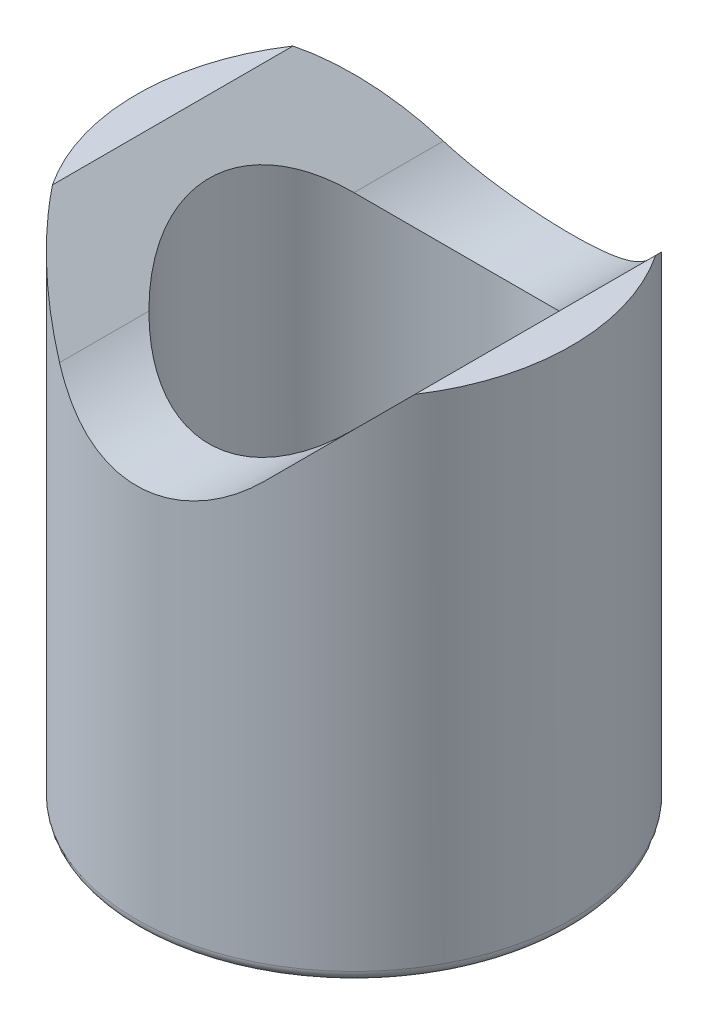
SolidWorks part; units mm, degrees
material "1060 Сплав"
ref_plane "Спереди" through (0, 0, 0) normal (0, 0, 1) x (1, 0, 0)
ref_plane "Сверху" through (0, 0, 0) normal (0, 1, 0) x (1, 0, 0)
ref_plane "Справа" through (0, 0, 0) normal (1, 0, 0) x (0, 0, -1)
sketch "Эскиз1" plane through (0, 0, 0) normal (0, 1, 0) x (1, 0, 0)
  circle A0 centre (0, 0) radius 6
  circle A1 centre (0, 0) radius 4
extrude "Бобышка-Вытянуть1" add sketch "Эскиз1" along normal blind 15
cosmetic thread "Условное изображение резьбы1" parameters "D2"=24
sketch "Эскиз2" plane through (0, 0, 0) normal (0, 0, 1) x (1, 0, 0)
  line L0 (5, 14) -> (2.8284, 11.8284)
  line L1 (-2.8284, 11.8284) -> (-5, 14)
  line L2 (6, 15) -> (-6, 15) construction
  line L3 (-5, 14) -> (-7.9166, 14)
  line L4 (5, 14) -> (8.0781, 14)
  line L5 (-7.9166, 14) -> (-7.9166, 18.7424)
  line L6 (-7.9166, 18.7424) -> (8.0781, 18.7424)
  line L7 (8.0781, 18.7424) -> (8.0781, 14)
  arc A0 (2.8284, 11.8284) -> (-2.8284, 11.8284) centre (0, 14.6569) cw
  point P12 (0, 9)
  dimension "D5" = 4
  dimension "D1" = 90
  dimension "D2" = 45
  dimension "D3" = 9
  dimension "D4" = 1
extrude "Вырез-Вытянуть1" cut sketch "Эскиз2" against normal through all and the other way through all
fillet "Скругление1" radius 0.3 1 edges at (0, 0, 6)
